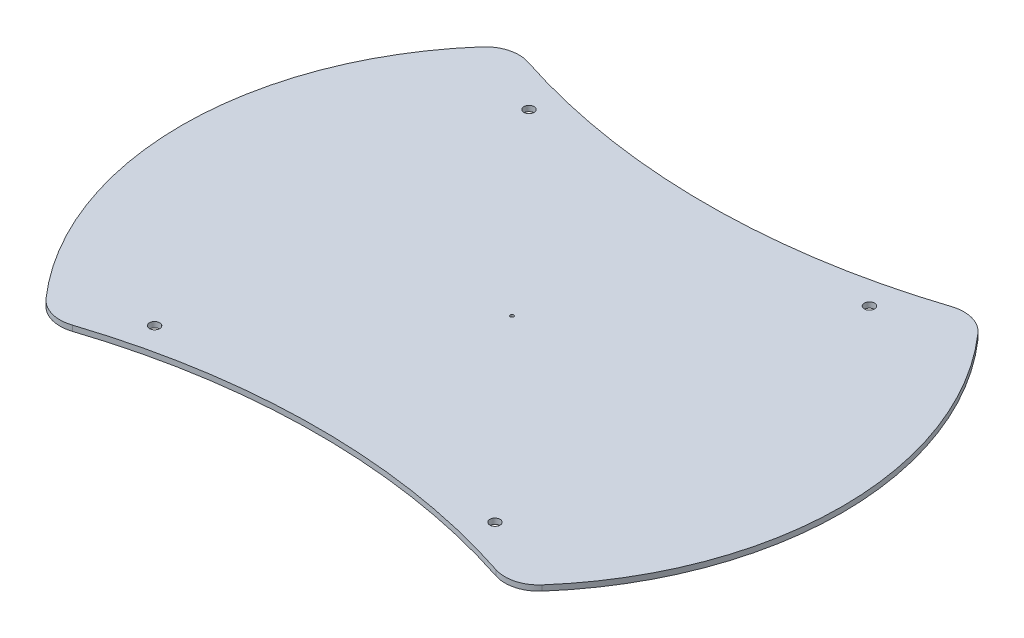
SolidWorks part; units mm, degrees
ref_plane "Plano frontal" through (0, 0, 0) normal (0, 0, 1) x (1, 0, 0)
ref_plane "Plano superior" through (0, 0, 0) normal (0, 1, 0) x (1, 0, 0)
ref_plane "Plano direito" through (0, 0, 0) normal (1, 0, 0) x (0, 0, -1)
sketch "Esboço1" plane through (0, 0, 0) normal (0, 1, 0) x (1, 0, 0)
  line L0 (0, 0) -> (0, 303.4641) construction
  line L1 (-180.7753, 0) -> (210.2784, 0) construction
  circle A0 centre (0, 0) radius 97
  circle A1 centre (0, 257) radius 200
  circle A2 centre (0, -257) radius 200
  circle A3 centre (0, 0) radius 0.5
  point P6 (0, 57)
  point P7 (0, 97)
  dimension "D1" = 194
  dimension "D2" = 400
  dimension "D3" = 40
extrude "Ressalto-extrusão1" add sketch "Esboço1" along normal blind 1.6 contours A0 A2 A1
fillet "Filete1" radius 10 4 edges at (-68.192, 0.8, -68.9844) (68.192, 0.8, -68.9844) (68.192, 0.8, 68.9844) (-68.192, 0.8, 68.9844)
sketch "Esboço2" plane through (0, 1.6, 0) normal (0, 1, 0) x (1, 0, 0)
  line L0 (0, 57) -> (0, -57) construction
  line L1 (-97, 0) -> (97, 0) construction
  circle A0 centre (-50, 55) radius 1.5
  arc A1 (-72.8649, 64.0289) -> (-72.8649, -64.0289) centre (0, 0) ccw construction
  arc A2 (72.8649, -64.0289) -> (72.8649, 64.0289) centre (0, 0) ccw construction
  arc A3 (-62.241, 66.9314) -> (62.241, 66.9314) centre (0, 257) ccw construction
  arc A4 (62.241, -66.9314) -> (-62.241, -66.9314) centre (0, -257) ccw construction
  dimension "D1" = 3
  dimension "D2" = 55
  dimension "D3" = 50
extrude "Corte-extrusão1" cut sketch "Esboço2" against normal through all
mirror "Espelhar1" about plane through (0, 0, 0) normal (1, 0, 0) of "Corte-extrusão1"
mirror "Espelhar2" about plane through (0, 0, 0) normal (0, 0, 1) of "Espelhar1", "Corte-extrusão1"
sketch "Esboço3" plane through (0, 1.6, 0) normal (0, 1, 0) x (-1, 0, 0)
  line L0 (-22.5282, -113.2569) -> (0, 0)
  line L1 (0, 0) -> (0, -75.304) construction
  line L2 (22.5282, -113.2569) -> (0, 0)
  line L3 (-64.1549, -96.0146) -> (0, 0)
  line L4 (-96.0146, -64.1549) -> (0, 0)
  line L5 (-113.2569, -22.5282) -> (0, 0)
  line L6 (-113.2569, 22.5282) -> (0, 0)
  line L7 (-96.0146, 64.1549) -> (0, 0)
  line L8 (-64.1549, 96.0146) -> (0, 0)
  line L9 (-22.5282, 113.2569) -> (0, 0)
  line L10 (22.5282, 113.2569) -> (0, 0)
  line L11 (64.1549, 96.0146) -> (0, 0)
  line L12 (96.0146, 64.1549) -> (0, 0)
  line L13 (113.2569, 22.5282) -> (0, 0)
  line L14 (113.2569, -22.5282) -> (0, 0)
  line L15 (96.0146, -64.1549) -> (0, 0)
  line L16 (64.1549, -96.0146) -> (0, 0)
  point P22 (0, 0)
  dimension "D1" = 11.25
  dimension "D2" = 16
sketch "Esboço4" plane through (0, 1.6, 0) normal (0, 1, 0) x (-1, 0, 0)
  line L0 (0, 0) -> (0, 74.1479) construction
  line L1 (0, 0) -> (36.4307, 87.9514)
  line L2 (0, 0) -> (87.9514, 36.4307)
  line L3 (0, 0) -> (87.9514, -36.4307)
  line L4 (0, 0) -> (36.4307, -87.9514)
  line L5 (0, 0) -> (-36.4307, -87.9514)
  line L6 (0, 0) -> (-87.9514, -36.4307)
  line L7 (0, 0) -> (-87.9514, 36.4307)
  line L8 (0, 0) -> (-36.4307, 87.9514)
  point P14 (0, 0)
  dimension "D1" = 22.5
  dimension "D2" = 8
